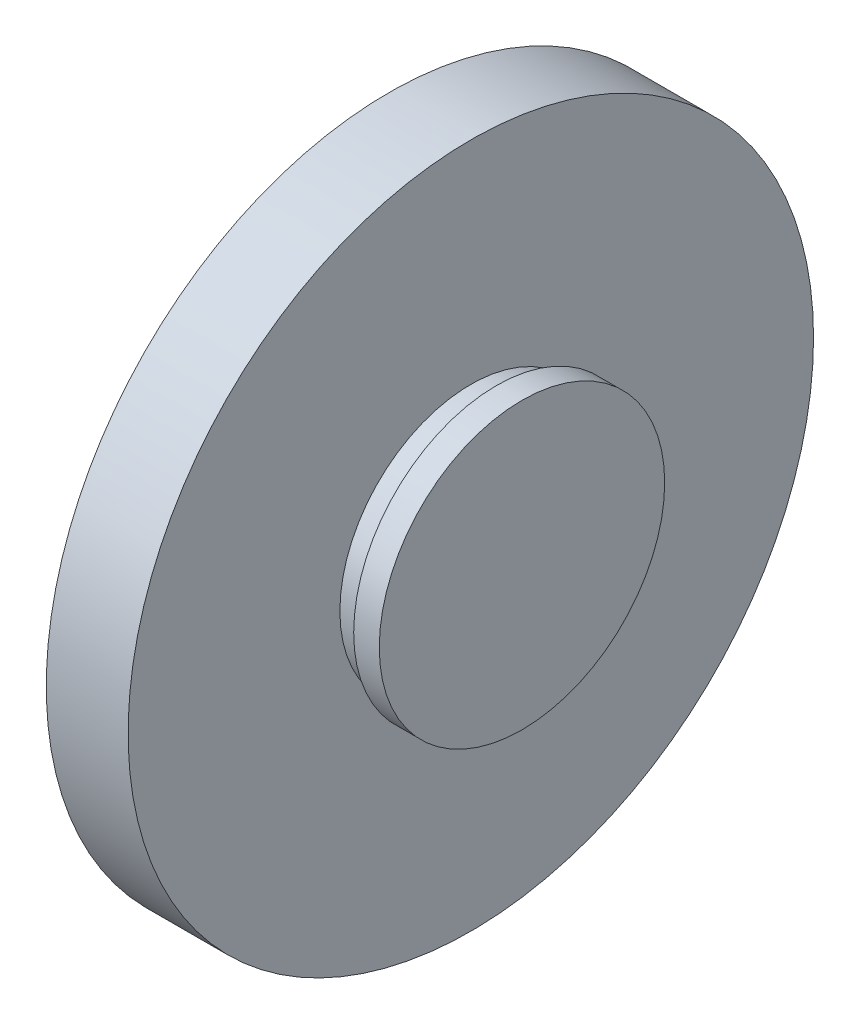
SolidWorks part; units mm, degrees
ref_plane "Front Plane" through (0, 0, 0) normal (0, 0, 1) x (1, 0, 0)
ref_plane "Top Plane" through (0, 0, 0) normal (0, 1, 0) x (1, 0, 0)
ref_plane "Right Plane" through (0, 0, 0) normal (1, 0, 0) x (0, 0, -1)
sketch "Sketch2" plane through (0, 0, 0) normal (1, 0, 0) x (0, 0, -1)
  circle A0 centre (0, 0) radius 17.9
  circle A1 centre (0, 0) radius 12.8
  circle A2 centre (0, 0) radius 33.5
  dimension "D1" = 35.8
  dimension "D2" = 25.6
  dimension "D3" = 67
extrude "Boss-Extrude1" add sketch "Sketch2" along normal blind 8 contours A2
sketch "Sketch7" plane through (8, 0, 0) normal (1, 0, 0) x (0, 0, -1)
  circle A0 centre (0, 0) radius 12.8
  dimension "D1" = 25.6
extrude "Boss-Extrude2" add sketch "Sketch7" along normal blind 2.5
sketch "Sketch8" plane through (10.5, 0, 0) normal (1, 0, 0) x (0, 0, -1)
  circle A0 centre (0, 0) radius 13.95
  dimension "D1" = 27.9
extrude "Boss-Extrude3" add sketch "Sketch8" along normal blind 2.5
sketch "Sketch10" plane through (0, 0, 0) normal (-1, 0, 0) x (0, 0, 1)
  line L0 (-4, -27.2039) -> (-6.5, -6.5)
  line L1 (-6.5, -6.5) -> (-27.2039, -4)
  line L2 (-27.2039, 4) -> (-6.5, 6.5)
  line L3 (-6.5, 6.5) -> (-4, 27.2039)
  line L4 (4, 27.2039) -> (6.5, 6.5)
  line L5 (6.5, 6.5) -> (27.2039, 4)
  line L6 (27.2039, -4) -> (6.5, -6.5)
  line L7 (6.5, -6.5) -> (4, -27.2039)
  line L8 (-6.5, 6.5) -> (6.5, 6.5) construction
  line L9 (6.5, 6.5) -> (6.5, -6.5) construction
  line L10 (6.5, -6.5) -> (-6.5, -6.5) construction
  line L11 (-6.5, 6.5) -> (-6.5, -6.5) construction
  line L12 (0, 0) -> (-6.5, 0) construction
  line L13 (0, 0) -> (0, -6.5) construction
  line L14 (-26.7209, 0) -> (-6.5, 0) construction
  line L15 (0, -26.7209) -> (0, -6.5) construction
  line L16 (26.7209, 0) -> (6.5, 0) construction
  line L17 (0, 6.5) -> (0, 26.7209) construction
  line L18 (-30.75, 0) -> (-26.7209, 0) construction
  line L19 (26.7209, 0) -> (30.75, 0) construction
  arc A0 (-27.2039, 4) -> (-27.2039, -4) centre (-26.7209, 0) ccw
  arc A1 (27.2039, 4) -> (27.2039, -4) centre (26.7209, 0) cw
  arc A2 (-4, 27.2039) -> (4, 27.2039) centre (0, 26.7209) cw
  arc A3 (4, -27.2039) -> (-4, -27.2039) centre (0, -26.7209) cw
  point P23 (0, 0)
  dimension "D1" = 61.5
  dimension "D2" = 13
  dimension "D3" = 8
extrude "Cut-Extrude1" cut sketch "Sketch10" against normal blind 5.5
sketch "Sketch11" plane through (5.5, 0, 0) normal (-1, 0, 0) x (0, 0, 1)
  circle A0 centre (0, 0) radius 6
  dimension "D1" = 12
extrude "Cut-Extrude2" cut sketch "Sketch11" against normal blind 3.2
